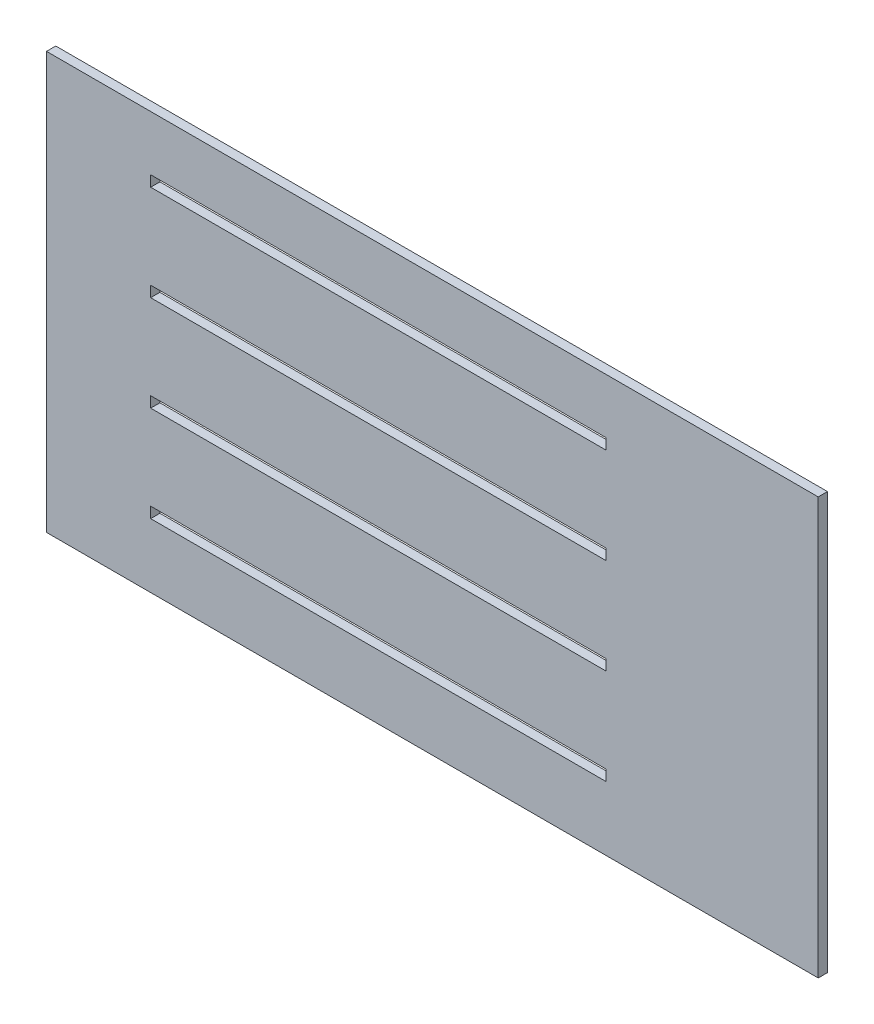
SolidWorks part; units mm, degrees
ref_plane "Front Plane" through (0, 0, 0) normal (0, 0, 1) x (1, 0, 0)
ref_plane "Top Plane" through (0, 0, 0) normal (0, 1, 0) x (1, 0, 0)
ref_plane "Right Plane" through (0, 0, 0) normal (1, 0, 0) x (0, 0, -1)
sketch "Sketch1" plane through (0, 0, 0) normal (0, 0, 1) x (1, 0, 0)
  line L2 (79.894, 76.2298) -> (148.894, 76.2298)
  line L6 (79.894, -58.7702) -> (148.894, -58.7702)
  line L7 (148.894, 76.2298) -> (148.894, -58.7702)
  line L11 (-67.1671, 76.2298) -> (79.894, 76.2298)
  line L15 (-67.1671, -58.7702) -> (79.894, -58.7702)
  line L17 (-67.1671, 76.2298) -> (-72.1671, 76.2298)
  line L19 (-67.1671, -58.7702) -> (-72.1671, -58.7702)
  line L21 (-72.1671, 76.2298) -> (-98.1671, 76.2298)
  line L23 (-72.1671, -58.7702) -> (-98.1671, -58.7702)
  line L25 (-98.1671, 76.2298) -> (-101.1671, 76.2298)
  line L27 (-98.1671, -58.7702) -> (-101.1671, -58.7702)
  line L28 (-101.1671, 76.2298) -> (-101.1671, -58.7702)
extrude "Boss-Extrude1" add sketch "Sketch1" against normal blind 3 contours L21 L25 L28 L27 L23 L19 L15 L6 L7 L2 L11 L17
sketch "Sketch3" plane through (0, 0, 0) normal (0, 0, 1) x (1, 0, 0)
  line L0 (-67.1671, -37.7702) -> (79.8329, -37.7702) construction
  line L1 (-67.1671, 58.2298) -> (79.8329, 58.2298)
  line L2 (-67.1671, 58.2298) -> (-67.1671, 55.2298)
  line L3 (-67.1671, 55.2298) -> (79.8329, 55.2298)
  line L4 (79.8329, 58.2298) -> (79.8329, 55.2298)
  line L5 (-67.1671, 27.2298) -> (79.8329, 27.2298)
  line L6 (-67.1671, 27.2298) -> (-67.1671, 24.2298)
  line L7 (-67.1671, 24.2298) -> (79.8329, 24.2298)
  line L8 (79.8329, 27.2298) -> (79.8329, 24.2298)
  line L9 (-67.1671, -3.7702) -> (79.8329, -3.7702)
  line L10 (-67.1671, -3.7702) -> (-67.1671, -6.7702)
  line L11 (-67.1671, -6.7702) -> (79.8329, -6.7702)
  line L12 (79.8329, -3.7702) -> (79.8329, -6.7702)
  line L13 (-67.1671, -34.7702) -> (79.8329, -34.7702)
  line L14 (-67.1671, -34.7702) -> (-67.1671, -37.7702)
  line L15 (-67.1671, -37.7702) -> (79.8329, -37.7702)
  line L16 (79.8329, -34.7702) -> (79.8329, -37.7702)
  line L17 (-67.4171, 58.4798) -> (80.0829, 58.4798)
  line L18 (80.0829, 58.4798) -> (80.0829, 54.9798)
  line L19 (-67.4171, 54.9798) -> (80.0829, 54.9798)
  line L20 (-67.4171, 58.4798) -> (-67.4171, 54.9798)
  line L21 (-67.4171, 27.4798) -> (80.0829, 27.4798)
  line L22 (80.0829, 27.4798) -> (80.0829, 23.9798)
  line L23 (-67.4171, 23.9798) -> (80.0829, 23.9798)
  line L24 (-67.4171, 27.4798) -> (-67.4171, 23.9798)
  line L25 (-67.4171, -3.5202) -> (80.0829, -3.5202)
  line L26 (80.0829, -3.5202) -> (80.0829, -7.0202)
  line L27 (-67.4171, -7.0202) -> (80.0829, -7.0202)
  line L28 (-67.4171, -3.5202) -> (-67.4171, -7.0202)
  line L29 (-67.4171, -34.5202) -> (80.0829, -34.5202)
  line L30 (80.0829, -34.5202) -> (80.0829, -38.0202)
  line L31 (-67.4171, -38.0202) -> (80.0829, -38.0202)
  line L32 (-67.4171, -34.5202) -> (-67.4171, -38.0202)
  dimension "D1" = 0.25
extrude "Cut-Extrude2" cut sketch "Sketch3" against normal blind 3
